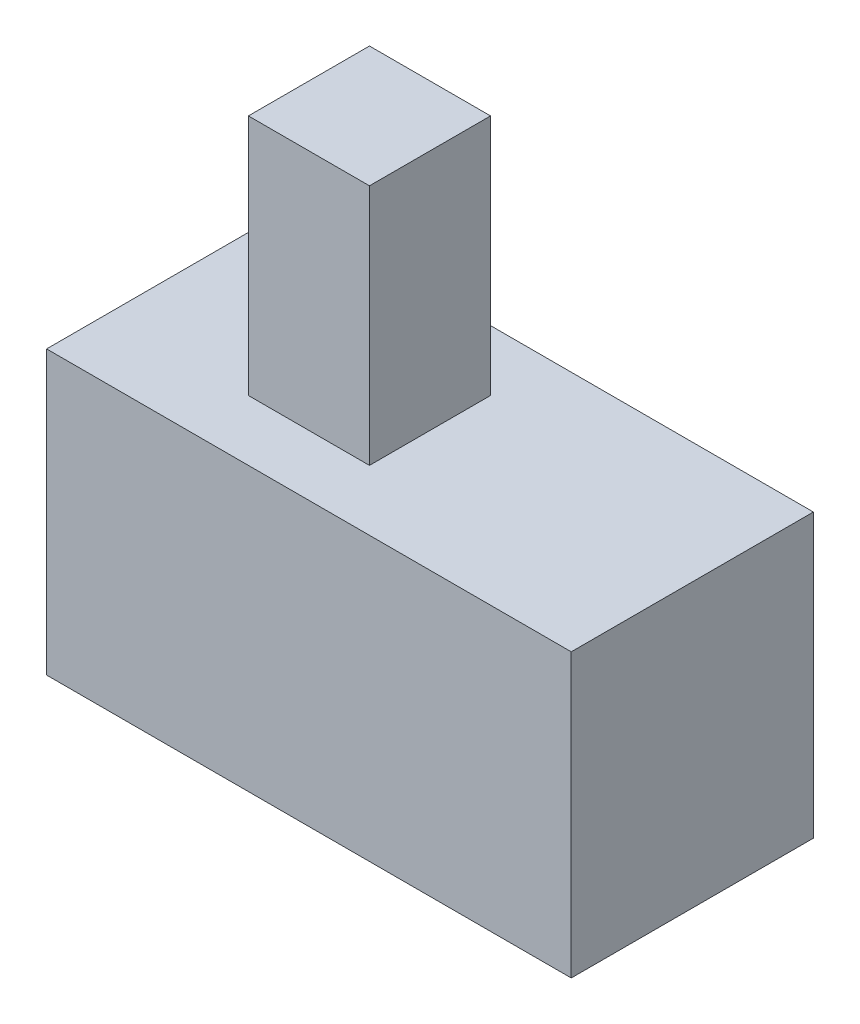
SolidWorks part; units mm, degrees
ref_plane "Front Plane" through (0, 0, 0) normal (0, 0, 1) x (1, 0, 0)
ref_plane "Top Plane" through (0, 0, 0) normal (0, 1, 0) x (1, 0, 0)
ref_plane "Right Plane" through (0, 0, 0) normal (1, 0, 0) x (0, 0, -1)
sketch "Sketch1" plane through (0, 0, 0) normal (0, 0, 1) x (1, 0, 0)
  line L1 (-6.5, 3.5) -> (6.5, 3.5)
  line L2 (-6.5, 3.5) -> (-6.5, -3.5)
  line L3 (-6.5, -3.5) -> (6.5, -3.5)
  line L4 (6.5, 3.5) -> (6.5, -3.5)
  line L5 (-6.5, 3.5) -> (6.5, -3.5) construction
  line L6 (-6.5, -3.5) -> (6.5, 3.5) construction
  point P0 (0, 0)
  dimension "D1" = 13
  dimension "D2" = 7
extrude "Boss-Extrude1" add sketch "Sketch1" along normal blind 6
sketch "Sketch2" plane through (0, 3.5, 0) normal (0, 1, 0) x (1, 0, 0)
  line L0 (-1.5, -3) -> (-6.5, -3) construction
  line L1 (-3, -1.5) -> (0, -1.5)
  line L2 (-3, -1.5) -> (-3, -4.5)
  line L3 (-3, -4.5) -> (0, -4.5)
  line L4 (0, -1.5) -> (0, -4.5)
  line L5 (-3, -1.5) -> (0, -4.5) construction
  line L6 (-3, -4.5) -> (0, -1.5) construction
  line L7 (-6.5, -6) -> (-6.5, 0) construction
  point P0 (-1.5, -3)
  dimension "D1" = 3
extrude "Boss-Extrude2" add sketch "Sketch2" along normal blind 6
